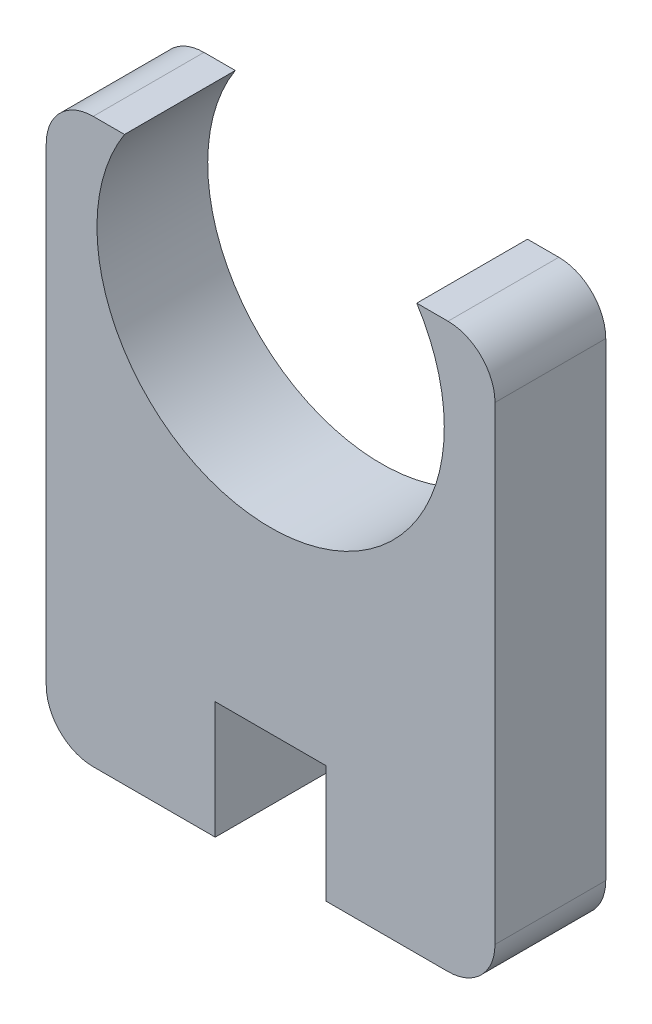
SolidWorks part; units mm, degrees
material "Acrylic (Medium-high impact)"
ref_plane "Front Plane" through (0, 0, 0) normal (0, 0, 1) x (1, 0, 0)
ref_plane "Top Plane" through (0, 0, 0) normal (0, 1, 0) x (1, 0, 0)
ref_plane "Right Plane" through (0, 0, 0) normal (1, 0, 0) x (0, 0, -1)
sketch "Sketch1" plane through (0, 0, 0) normal (0, 0, 1) x (1, 0, 0)
  line L0 (0, 0) -> (0, 15.24)
  line L1 (0, 15.24) -> (2.1172, 15.24)
  line L2 (12.1412, 15.24) -> (12.1412, 0)
  line L3 (12.1412, 0) -> (7.5692, 0)
  line L4 (7.5692, 0) -> (7.5692, 3.175)
  line L5 (7.5692, 3.175) -> (4.572, 3.175)
  line L6 (4.572, 3.175) -> (4.572, 0)
  line L7 (4.572, 0) -> (0, 0)
  line L8 (10.024, 15.24) -> (12.1412, 15.24)
  arc A0 (2.1172, 15.24) -> (10.024, 15.24) centre (6.0706, 12.7) ccw
  point P11 (6.0706, 3.175)
  dimension "D4" = 9.398
  dimension "D1" = 4.572
  dimension "D2" = 15.24
  dimension "D3" = 3.175
  dimension "D5" = 9.525
  dimension "D6" = 2.9972
extrude "Boss-Extrude1" add sketch "Sketch1" along normal blind 2.9972
fillet "Fillet1" radius 1.27 4 edges at (12.1412, 15.24, 1.4986) (0, 15.24, 1.4986) (12.1412, 0, 1.4986) (0, 0, 1.4986)
